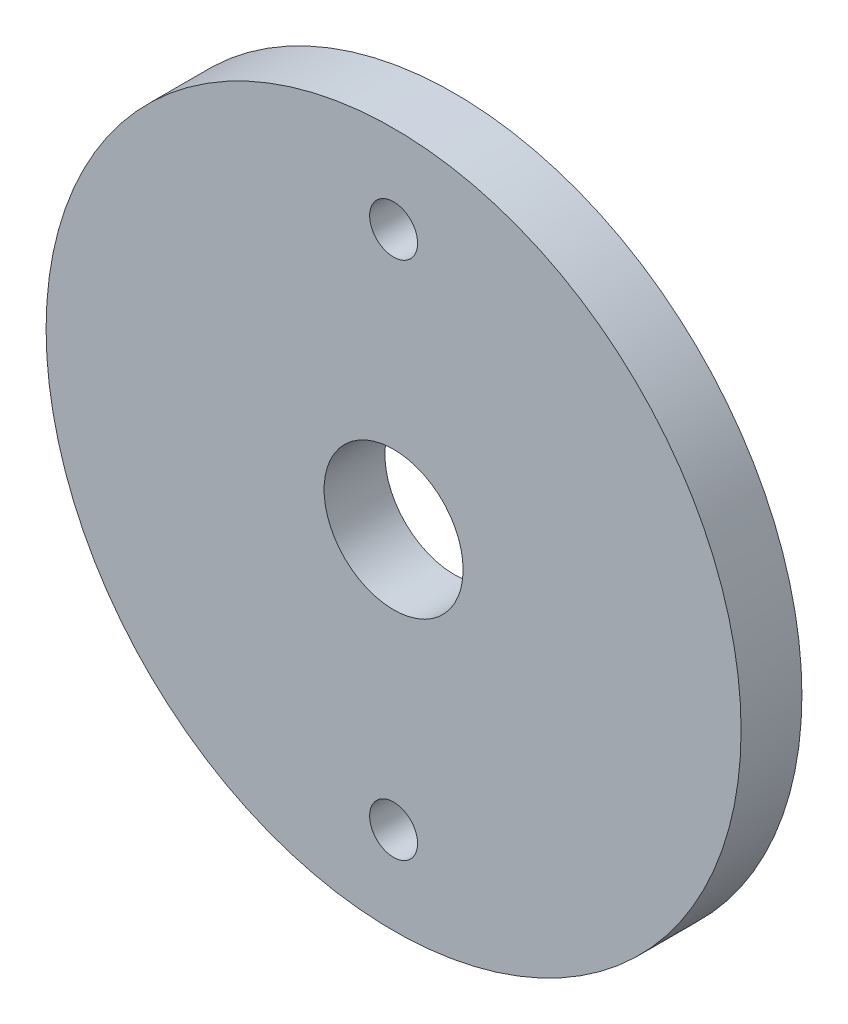
SolidWorks part; units mm, degrees
material "Cedar"
ref_plane "Front Plane" through (0, 0, 0) normal (0, 0, 1) x (1, 0, 0)
ref_plane "Top Plane" through (0, 0, 0) normal (0, 1, 0) x (1, 0, 0)
ref_plane "Right Plane" through (0, 0, 0) normal (1, 0, 0) x (0, 0, -1)
sketch "Sketch1" plane through (0, 0, 0) normal (0, 0, 1) x (1, 0, 0)
  circle A0 centre (0, 0) radius 25.4
  circle A1 centre (0, 0) radius 5.08
  circle A2 centre (0, 18.9992) radius 1.7526
  circle A3 centre (0, -18.9992) radius 1.7526
  dimension "D1" = 50.8
  dimension "D2" = 10.16
  dimension "D3" = 3.5052
  dimension "D5" = 3.5052
  dimension "D4" = 18.9992
  dimension "D6" = 18.9992
extrude "Boss-Extrude1" add sketch "Sketch1" along normal blind 4.445
